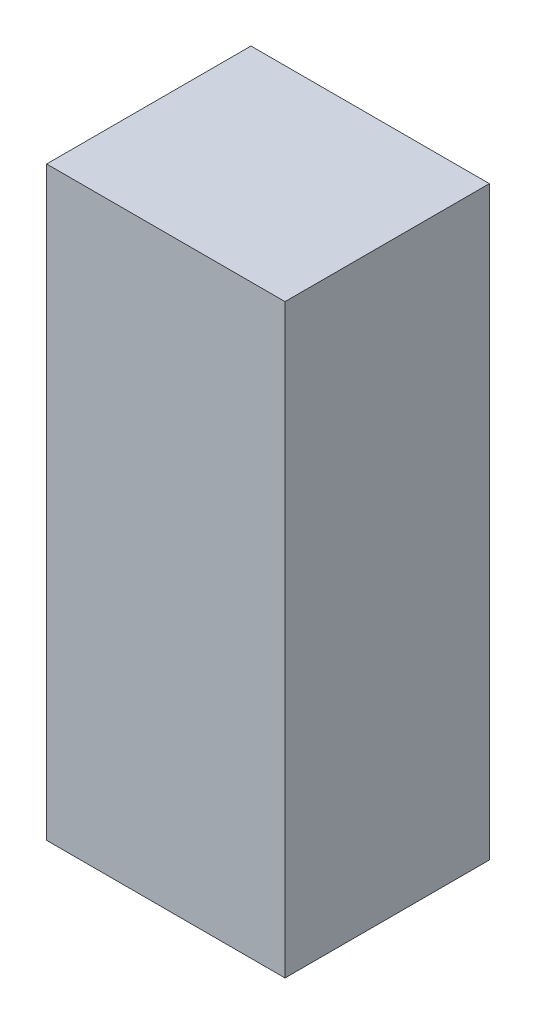
SolidWorks part; units mm, degrees
ref_plane "Front Plane" through (0, 0, 0) normal (0, 0, 1) x (1, 0, 0)
ref_plane "Top Plane" through (0, 0, 0) normal (0, 1, 0) x (1, 0, 0)
ref_plane "Right Plane" through (0, 0, 0) normal (1, 0, 0) x (0, 0, -1)
sketch "Sketch1" plane through (0, 0, 0) normal (0, 1, 0) x (1, 0, 0)
  line L1 (0, 0) -> (350, 0)
  line L2 (0, 0) -> (0, -300)
  line L3 (0, -300) -> (350, -300)
  line L4 (350, 0) -> (350, -300)
  dimension "D1" = 350
  dimension "D2" = 300
extrude "Boss-Extrude1" add sketch "Sketch1" along normal blind 610 and the other way blind 250
